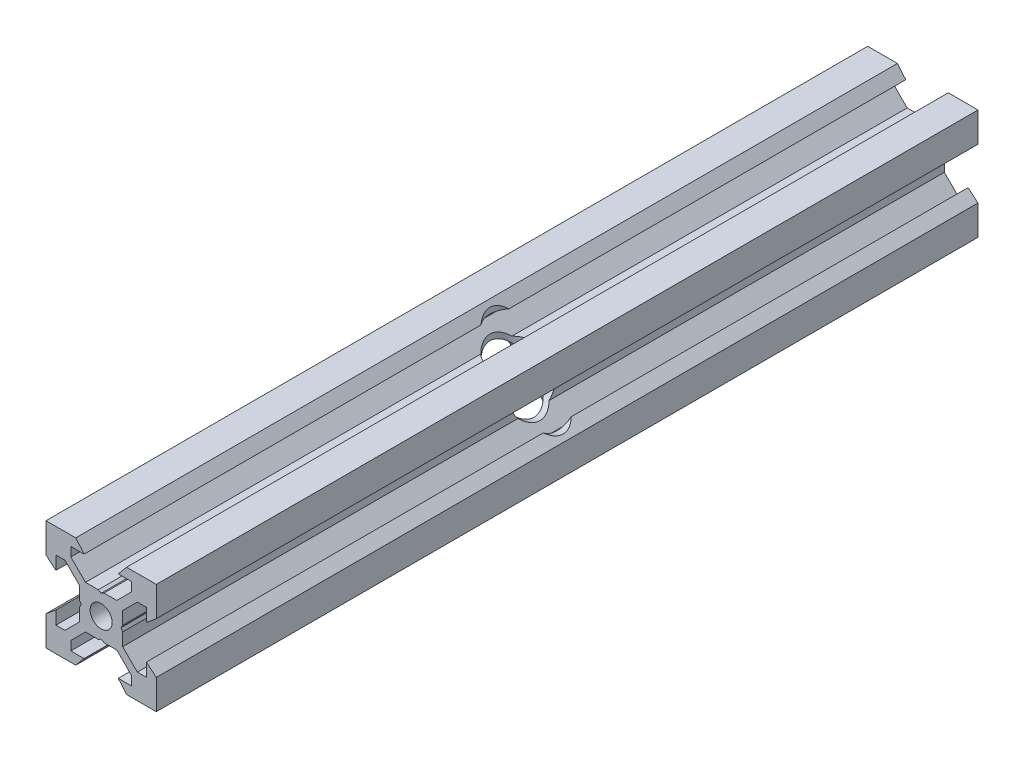
SolidWorks part; units mm, degrees
material "3.3535 (EN-AW 5754)"
ref_plane "Front Plane" through (0, 0, 0) normal (0, 0, 1) x (1, 0, 0)
ref_plane "Top Plane" through (0, 0, 0) normal (0, 1, 0) x (1, 0, 0)
ref_plane "Right Plane" through (0, 0, 0) normal (1, 0, 0) x (0, 0, -1)
sketch "Sketch1" plane through (0, 0, 0) normal (0, 0, 1) x (1, 0, 0)
  line L0 (10, 10) -> (4.6104, 10) construction
  line L1 (10, 10) -> (10, 4.6104) construction
  line L2 (10, -10) -> (10, -4.6104) construction
  line L3 (10, -10) -> (4.6104, -10) construction
  line L4 (10, 10) -> (10, 4.6104)
  line L5 (6.5607, 5.5) -> (8.2, 5.5)
  line L6 (5.5, 8.2) -> (5.5, 6.5607)
  line L7 (10, 10) -> (4.6104, 10)
  line L8 (10, 10) -> (10, 4.6104)
  line L9 (6.5607, 5.5) -> (3.9, 2.8393)
  line L10 (5.5, 6.5607) -> (2.8393, 3.9)
  line L11 (10, 4.6104) -> (8.2, 3.1)
  line L12 (4.6104, 10) -> (3.1, 8.2)
  line L13 (8.2, 3.1) -> (8.2, 5.5)
  line L14 (3.1, 8.2) -> (5.5, 8.2)
  line L15 (-6.5607, 5.5) -> (-8.2, 5.5)
  line L16 (6.5607, -5.5) -> (8.2, -5.5)
  line L17 (3.1, -8.2) -> (5.5, -8.2)
  line L18 (8.2, -3.1) -> (8.2, -5.5)
  line L19 (4.6104, -10) -> (3.1, -8.2)
  line L20 (10, -4.6104) -> (8.2, -3.1)
  line L21 (0.5196, -3.9) -> (0, -3.6)
  line L22 (0.5196, 3.9) -> (0, 3.6)
  line L23 (3.6, 0) -> (3.9, -0.5196)
  line L24 (3.9, 0.5196) -> (3.6, 0)
  line L25 (3.9, 0.5196) -> (3.9, 2.8393)
  line L26 (2.8393, 3.9) -> (0.5196, 3.9)
  line L27 (3.9, -2.8393) -> (3.9, -0.5196)
  line L28 (2.8393, -3.9) -> (0.5196, -3.9)
  line L29 (5.5, -6.5607) -> (2.8393, -3.9)
  line L30 (6.5607, -5.5) -> (3.9, -2.8393)
  line L31 (10, -10) -> (10, -4.6104)
  line L32 (10, -10) -> (4.6104, -10)
  line L33 (5.5, -8.2) -> (5.5, -6.5607)
  line L34 (-6.5607, -5.5) -> (-8.2, -5.5)
  line L35 (10, -10) -> (10, -4.6104)
  line L36 (0, 0) -> (0, 8.2) construction
  line L37 (-10, -10) -> (-4.6104, -10) construction
  line L38 (-10, -10) -> (-10, -4.6104) construction
  line L39 (-10, 10) -> (-10, 4.6104) construction
  line L40 (-10, 10) -> (-4.6104, 10) construction
  line L41 (-10, -10) -> (-10, -4.6104)
  line L43 (-5.5, -8.2) -> (-5.5, -6.5607)
  line L44 (-10, -10) -> (-4.6104, -10)
  line L45 (-10, -10) -> (-10, -4.6104)
  line L46 (-6.5607, -5.5) -> (-3.9, -2.8393)
  line L47 (-5.5, -6.5607) -> (-2.8393, -3.9)
  line L48 (-2.8393, -3.9) -> (-0.5196, -3.9)
  line L49 (-3.9, -2.8393) -> (-3.9, -0.5196)
  line L50 (-2.8393, 3.9) -> (-0.5196, 3.9)
  line L51 (-3.9, 0.5196) -> (-3.9, 2.8393)
  line L52 (-3.9, 0.5196) -> (-3.6, 0)
  line L53 (-3.6, 0) -> (-3.9, -0.5196)
  line L54 (-0.5196, 3.9) -> (0, 3.6)
  line L55 (-0.5196, -3.9) -> (0, -3.6)
  line L56 (-10, -4.6104) -> (-8.2, -3.1)
  line L57 (-4.6104, -10) -> (-3.1, -8.2)
  line L58 (-8.2, -3.1) -> (-8.2, -5.5)
  line L59 (-3.1, -8.2) -> (-5.5, -8.2)
  line L60 (-10, -10) -> (10, -10) construction
  line L61 (-10, -10) -> (-10, 10) construction
  line L62 (-3.1, 8.2) -> (-5.5, 8.2)
  line L63 (-8.2, 3.1) -> (-8.2, 5.5)
  line L64 (-4.6104, 10) -> (-3.1, 8.2)
  line L65 (-10, 4.6104) -> (-8.2, 3.1)
  line L66 (-5.5, 6.5607) -> (-2.8393, 3.9)
  line L67 (-6.5607, 5.5) -> (-3.9, 2.8393)
  line L68 (-10, 10) -> (-10, 4.6104)
  line L69 (-10, 10) -> (-4.6104, 10)
  line L70 (-5.5, 8.2) -> (-5.5, 6.5607)
  line L71 (-10, 10) -> (10, 10) construction
  line L72 (-10, 10) -> (-10, 4.6104)
  line L73 (10, -10) -> (10, 10) construction
  line L74 (-10, -10) -> (10, 10) construction
  line L75 (-10, 10) -> (10, -10) construction
  circle A0 centre (0, 0) radius 2
  dimension "D7" = 4
  dimension "D1" = 20
  dimension "D2" = 5.3896
  dimension "D3" = 4.5
  dimension "D4" = 50
  dimension "D5" = 1.8
  dimension "D6" = 1.5104
  dimension "D8" = 5.5
  dimension "D9" = 120
  dimension "D10" = 0.3
  dimension "D11" = 2.3197
  dimension "D12" = 7.8
  dimension "D13" = 7.8
  dimension "D14" = 1.5
  dimension "D15" = 2.6607
extrude "Boss-Extrude1" add sketch "Sketch1" along normal blind 149 contours L70 L62 L64 L69 L68 L65 L63 L15 L67 L51 L52 L53 L49 L46 L34 L58 L56 L41 L44 L57 L59 L43 L47 L48 L55 L21 L28 L29 L33 L17 L19 L32 L31 L20 L18 L16 L30 L27 L23 L24 L25 L9 L5 L13 L11 L4 L7 L12 L14 L6 L10
sketch "Sketch4" plane through (0, 0, 0) normal (1, 0, 0) x (0, 0, -1)
  line L0 (-149, 0) -> (0, 0) construction
  circle A0 centre (-74.5, 0) radius 4
  dimension "D1" = 8
extrude "Cut-Extrude1" cut sketch "Sketch4" against normal through all both and the other way through all
sketch "Sketch5" plane through (0, 0, 0) normal (0, 1, 0) x (1, 0, 0)
  line L0 (0, 0) -> (0, -149) construction
  circle A0 centre (0, -74.5) radius 4
  dimension "D1" = 8
extrude "Cut-Extrude2" cut sketch "Sketch5" against normal through all both and the other way through all
sketch "Sketch6" [suppressed] plane through (0, 0, 0) normal (1, 0, 0) x (0, 0, -1)
  circle A0 centre (-70.53, 22.36) radius 18
extrude "Cut_MotorBossNotch" [suppressed] cut sketch "Sketch6" against normal through all and the other way through all
